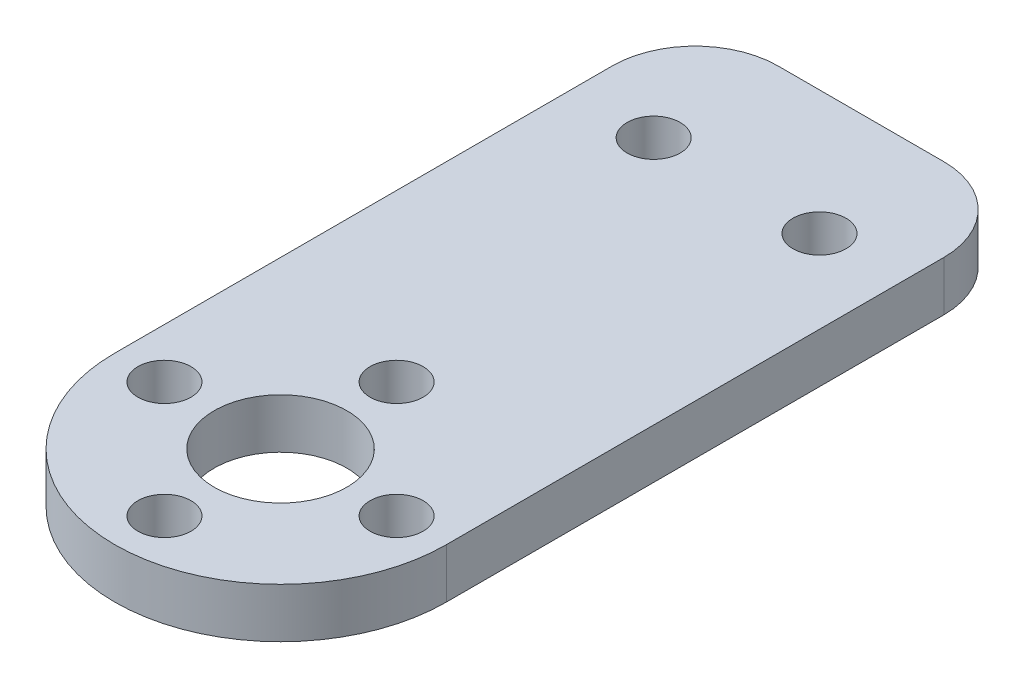
SolidWorks part; units mm, degrees
ref_plane "前视基准面" through (0, 0, 0) normal (0, 0, 1) x (1, 0, 0)
ref_plane "上视基准面" through (0, 0, 0) normal (0, 1, 0) x (1, 0, 0)
ref_plane "右视基准面" through (0, 0, 0) normal (1, 0, 0) x (0, 0, -1)
sketch "草图1" plane through (0, 0, 0) normal (0, 1, 0) x (1, 0, 0)
  line L0 (-10, 0) -> (10, 0) construction
  line L1 (-10, 0) -> (-10, 35)
  line L2 (-10, 35) -> (10, 35)
  line L3 (10, 35) -> (10, 0)
  line L4 (-10, 27.5) -> (-5, 27.5) construction
  line L5 (-5, 27.5) -> (5, 27.5) construction
  line L6 (5, 27.5) -> (10, 27.5) construction
  arc A1 (10, 0) -> (-10, 0) centre (0, 0) cw
  circle A2 centre (-5, 27.5) radius 1.6
  circle A3 centre (5, 27.5) radius 1.6
  circle A4 centre (0, 0) radius 7 construction
  circle A5 centre (0, 7) radius 1.6
  circle A6 centre (-7, 0) radius 1.6
  circle A7 centre (0, -7) radius 1.6
  circle A8 centre (7, 0) radius 1.6
  circle A9 centre (0, 0) radius 4
  dimension "D1" = 20
  dimension "D2" = 3.2
  dimension "D6" = 14
  dimension "D7" = 3.2
  dimension "D8" = 8
  dimension "D3" = 7.5
  dimension "D4" = 10
  dimension "D5" = 35
extrude "凸台-拉伸1" add sketch "草图1" along normal blind 3
fillet "圆角1" radius 5 2 edges at (10, 1.5, -35) (-10, 1.5, -35)
